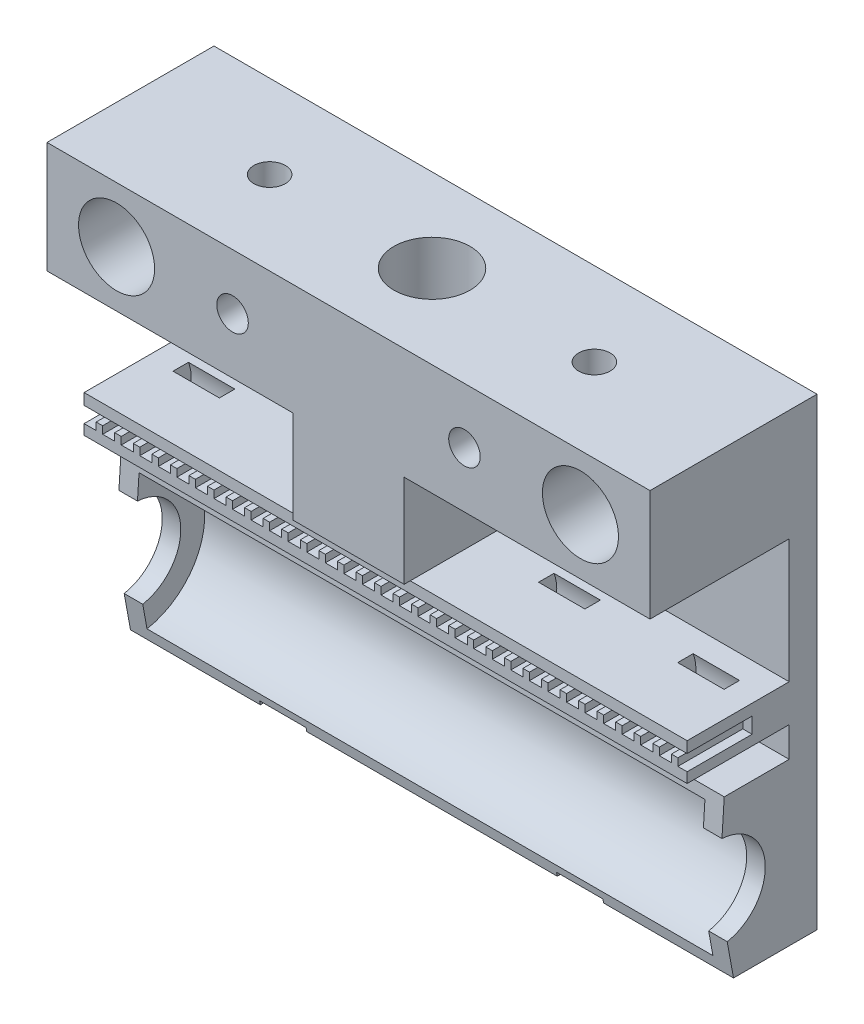
SolidWorks part; units mm, degrees
ref_plane "Ebene vorne" through (0, 0, 0) normal (0, 0, 1) x (1, 0, 0)
ref_plane "Ebene oben" through (0, 0, 0) normal (0, 1, 0) x (1, 0, 0)
ref_plane "Ebene rechts" through (0, 0, 0) normal (1, 0, 0) x (0, 0, -1)
sketch "Skizze1" plane through (0, 0, 0) normal (0, 0, 1) x (1, 0, 0)
  line L1 (-32.5, 25) -> (32.5, 25)
  line L2 (-32.5, 25) -> (-32.5, -25)
  line L3 (-32.5, -25) -> (32.5, -25)
  line L4 (32.5, 25) -> (32.5, -25)
  line L5 (-32.5, 25) -> (32.5, -25) construction
  line L6 (-32.5, -25) -> (32.5, 25) construction
  point P0 (0, 0)
  dimension "D1" = 65
  dimension "D2" = 50
extrude "Aufsatz-Linear austragen1" add sketch "Skizze1" along normal blind 3
sketch "Skizze2" plane through (0, 0, 3) normal (0, 0, 1) x (1, 0, 0)
  line L0 (32.5, -25) -> (32.5, 25) construction
  line L1 (-32.5, 25) -> (32.5, 25)
  line L2 (-32.5, 25) -> (-32.5, 13)
  line L3 (-32.5, 13) -> (32.5, 13)
  line L4 (32.5, 25) -> (32.5, 13)
  dimension "D1" = 12
extrude "Aufsatz-Linear austragen2" add sketch "Skizze2" along normal blind 15
sketch "Skizze3" plane through (0, 0, 18) normal (0, 0, 1) x (1, 0, 0)
  line L0 (32.5, 25) -> (-32.5, 25) construction
  line L1 (-32.5, 25) -> (-32.5, 13) construction
  line L2 (32.5, 13) -> (32.5, 25) construction
  circle A0 centre (-25, 19) radius 4.1
  circle A1 centre (25, 19) radius 4.1
  circle A2 centre (-12.5, 19) radius 1.7
  circle A3 centre (12.5, 19) radius 1.7
  point P6 (0, 25)
  dimension "D3" = 8.2
  dimension "D6" = 3.4
  dimension "D1" = 50
  dimension "D2" = 25
  dimension "D4" = 20
  dimension "D5" = 20
extrude "Schnitt-Linear austragen1" cut sketch "Skizze3" against normal up to next
sketch "Skizze4" plane through (0, 0, 0) normal (0, 0, -1) x (-1, 0, 0)
  line L0 (-32.5, -25) -> (-32.5, 25) construction
  line L1 (32.5, 25) -> (32.5, -25) construction
  point P0 (-12.5, 19)
  point P1 (12.5, 19)
  dimension "D1" = 20
  dimension "D2" = 20
sketch "Skizze7" plane through (0, 0, 0) normal (0, 0, -1) x (-1, 0, 0)
  line L0 (-32.5, 25) -> (32.5, 25) construction
  line L1 (-9.2091, 19) -> (-10.8546, 21.85)
  line L2 (-10.8546, 21.85) -> (-14.1454, 21.85)
  line L3 (-14.1454, 21.85) -> (-15.7909, 19)
  line L4 (-15.7909, 19) -> (-14.1454, 16.15)
  line L5 (-14.1454, 16.15) -> (-10.8546, 16.15)
  line L6 (-10.8546, 16.15) -> (-9.2091, 19)
  line L7 (15.7909, 19) -> (14.1454, 21.85)
  line L8 (14.1454, 21.85) -> (10.8546, 21.85)
  line L9 (10.8546, 21.85) -> (9.2091, 19)
  line L10 (9.2091, 19) -> (10.8546, 16.15)
  line L11 (10.8546, 16.15) -> (14.1454, 16.15)
  line L12 (14.1454, 16.15) -> (15.7909, 19)
  circle A0 centre (-12.5, 19) radius 2.85 construction
  circle A1 centre (12.5, 19) radius 2.85 construction
  dimension "D1" = 5.7
extrude "Schnitt-Linear austragen2" cut sketch "Skizze7" against normal blind 3.5
ref_plane "Ebene2" through (32.5, 0, 0) normal (-1, 0, 0) x (0, 0, 1)
sketch "Skizze10" plane through (32.5, 0, 0) normal (-1, 0, 0) x (0, 0, 1)
  line L0 (3, 13) -> (3, -25) construction
  line L2 (3, -25) -> (9, -25)
  line L3 (9, -25) -> (9.2184, -23.8)
  line L4 (3, -7.5887) -> (10, -7.5887)
  line L5 (10, -7.5887) -> (10.0788, -8.7887)
  line L6 (3, -7.5887) -> (3, -25)
  circle A0 centre (10.575, -16.3475) radius 7.575
  dimension "D1" = 15.15
  dimension "D3" = 6
  dimension "D4" = 7
  dimension "D5" = 1.2
  dimension "D6" = 1.2
extrude "Aufsatz-Linear austragen4" add sketch "Skizze10" along normal up to vertex (65 mm away) contours A0 L5 L4 L6 | A0 L6 L2 L3 up to point (-32.5, -25, 3)
sketch "Skizze11" plane through (32.5, 0, 0) normal (-1, 0, 0) x (0, 0, 1)
  line L0 (3, -7.5887) -> (10, -7.5887)
  line L1 (10, -7.5887) -> (10.2475, -11.3582)
  line L2 (3, -7.5887) -> (3, -25)
  line L3 (9, -25) -> (0, -25) construction
  line L4 (3, -25) -> (9, -25)
  line L5 (9, -25) -> (9.6796, -21.2666)
  circle A0 centre (10.575, -16.3475) radius 5
  dimension "D1" = 10
extrude "Aufsatz-Linear austragen5" add sketch "Skizze11" along normal blind 2 contours A0 L1 L0 L2 L4 L5
ref_plane "Ebene3" through (0, 0, 0) normal (1, 0, 0) x (0, 0, -1)
mirror "Spiegeln1" about plane through (0, 0, 0) normal (1, 0, 0) of "Aufsatz-Linear austragen5"
ref_axis "Achse1" through (-30.5, -16.3475, 10.575) along (1, 0, 0)
sketch "Skizze12" plane through (0, 0.6211, 9.461) normal (0, 0.0655, 0.9979) x (1, 0, 0)
  line L1 (-18.5, -7.1301) -> (-13.5, -7.1301)
  line L2 (-18.5, -7.1301) -> (-18.5, -8.6301)
  line L3 (-18.5, -8.6301) -> (-13.5, -8.6301)
  line L4 (-13.5, -7.1301) -> (-13.5, -8.6301)
  line L5 (-18.5, -7.1301) -> (-13.5, -8.6301) construction
  line L6 (-18.5, -8.6301) -> (-13.5, -7.1301) construction
  line L7 (0, -4.95) -> (0, 4.95) construction
  line L8 (-30.5, -9.4301) -> (30.5, -9.4301) construction
  point P0 (-16, -8.2275)
  dimension "D1" = 5
  dimension "D2" = 1.5
  dimension "D3" = 16
  dimension "D4" = 0.8
revolve "Schnitt-Rotation1" cut sketch "Skizze12" angle 360 about axis through (-30.5, -16.3475, 10.575) along (1, 0, 0)
mirror "Spiegeln2" about plane through (0, 0, 0) normal (1, 0, 0) of "Schnitt-Rotation1"
sketch "Skizze13" plane through (0, 0.6211, 9.461) normal (0, 0.0655, 0.9979) x (1, 0, 0)
  line L0 (-30.5, -9.4301) -> (30.5, -9.4301) construction
  line L1 (-17.3, -9.4301) -> (-16.5, -9.4301)
  line L2 (-17.3, -9.4301) -> (-17.3, -9.6301)
  line L3 (-17.3, -9.6301) -> (-16.5, -9.6301)
  line L4 (-16.5, -9.4301) -> (-16.5, -9.6301)
  line L5 (0, -4.95) -> (0, 4.95) construction
  dimension "D1" = 16.5
  dimension "D2" = 0.8
  dimension "D3" = 0.2
revolve "Rotation1" [suppressed] add sketch "Skizze13" about axis through (-30.5, -16.3475, 10.575) along (1, 0, 0)
mirror "Spiegeln3" [suppressed] about plane through (0, 0, 0) normal (1, 0, 0)
sketch "Skizze14" plane through (0, 0, 3) normal (0, 0, 1) x (1, 0, 0)
  line L0 (-32.5, 13) -> (-32.5, -7.5887) construction
  line L1 (-32.5, -0.3475) -> (32.5, -0.3475)
  line L2 (-32.5, -0.3475) -> (-32.5, -4.3475)
  line L3 (-32.5, -4.3475) -> (32.5, -4.3475)
  line L4 (32.5, -0.3475) -> (32.5, -4.3475)
  line L5 (32.5, 9.9) -> (32.5, -9.9) construction
  line L6 (-30.5, -16.3475) -> (30.5, -16.3475) construction
  point P10 (-32.5, -2.3475)
  dimension "D1" = 14
  dimension "D2" = 4
extrude "Aufsatz-Linear austragen6" add sketch "Skizze14" along normal blind 4
sketch "Skizze15" plane through (0, 0, 7) normal (0, 0, 1) x (1, 0, 0)
  line L0 (32.5, 9.9) -> (32.5, -9.9) construction
  line L1 (-32.5, -0.3475) -> (32.5, -0.3475)
  line L2 (-32.5, -0.3475) -> (-32.5, -1.5475)
  line L3 (-32.5, -1.5475) -> (32.5, -1.5475)
  line L4 (32.5, -0.3475) -> (32.5, -1.5475)
  line L6 (-32.5, -4.3475) -> (32.5, -4.3475)
  line L7 (-32.5, -4.3475) -> (-32.5, -2.4475)
  line L8 (-32.5, -2.4475) -> (32.5, -2.4475)
  line L9 (32.5, -4.3475) -> (32.5, -2.4475)
  dimension "D1" = 1.2
  dimension "D2" = 0.9
extrude "Aufsatz-Linear austragen7" add sketch "Skizze15" along normal blind 7
sketch "Skizze16" plane through (0, 0, 14) normal (0, 0, 1) x (1, 0, 0)
  line L0 (-32.5, -3.2475) -> (-31.2, -3.2475)
  line L1 (-32.5, -4.3475) -> (-32.5, -7.5887) construction
  line L2 (-31.2, -3.2475) -> (-31.2, -2.4475)
  line L3 (-31.2, -2.4475) -> (-30.5, -2.4475)
  line L4 (-30.5, -2.4475) -> (-30.5, -3.2475)
  line L5 (-30.5, -3.2475) -> (-29.2, -3.2475)
  line L6 (-29.2, -3.2475) -> (-29.2, -2.4475)
  line L7 (-29.2, -2.4475) -> (-28.5, -2.4475)
  line L8 (-28.5, -2.4475) -> (-28.5, -3.2475)
  line L10 (-28.5, -3.2475) -> (-27.2, -3.2475)
  line L11 (-27.2, -3.2475) -> (-27.2, -2.4475)
  line L12 (-27.2, -2.4475) -> (-26.5, -2.4475)
  line L13 (-26.5, -2.4475) -> (-26.5, -3.2475)
  line L14 (-25.2, -3.2475) -> (-25.2, -2.4475)
  line L15 (-25.2, -2.4475) -> (-24.5, -2.4475)
  line L16 (-24.5, -2.4475) -> (-24.5, -3.2475)
  line L17 (-26.5, -3.2475) -> (-25.2, -3.2475)
  line L18 (-24.5, -3.2475) -> (-23.2, -3.2475)
  line L19 (-23.2, -3.2475) -> (-23.2, -2.4475)
  line L20 (-23.2, -2.4475) -> (-22.5, -2.4475)
  line L21 (-22.5, -2.4475) -> (-22.5, -3.2475)
  line L22 (-21.2, -3.2475) -> (-21.2, -2.4475)
  line L23 (-21.2, -2.4475) -> (-20.5, -2.4475)
  line L24 (-20.5, -2.4475) -> (-20.5, -3.2475)
  line L25 (-22.5, -3.2475) -> (-21.2, -3.2475)
  line L26 (-20.5, -3.2475) -> (-19.2, -3.2475)
  line L27 (-19.2, -3.2475) -> (-19.2, -2.4475)
  line L28 (-19.2, -2.4475) -> (-18.5, -2.4475)
  line L29 (-18.5, -2.4475) -> (-18.5, -3.2475)
  line L30 (-17.2, -3.2475) -> (-17.2, -2.4475)
  line L31 (-17.2, -2.4475) -> (-16.5, -2.4475)
  line L32 (-16.5, -2.4475) -> (-16.5, -3.2475)
  line L33 (-18.5, -3.2475) -> (-17.2, -3.2475)
  line L34 (-16.5, -3.2475) -> (-15.2, -3.2475)
  line L35 (-15.2, -3.2475) -> (-15.2, -2.4475)
  line L36 (-15.2, -2.4475) -> (-14.5, -2.4475)
  line L37 (-14.5, -2.4475) -> (-14.5, -3.2475)
  line L38 (-13.2, -3.2475) -> (-13.2, -2.4475)
  line L39 (-13.2, -2.4475) -> (-12.5, -2.4475)
  line L40 (-12.5, -2.4475) -> (-12.5, -3.2475)
  line L41 (-14.5, -3.2475) -> (-13.2, -3.2475)
  line L42 (-12.5, -3.2475) -> (-11.2, -3.2475)
  line L43 (-11.2, -3.2475) -> (-11.2, -2.4475)
  line L44 (-11.2, -2.4475) -> (-10.5, -2.4475)
  line L45 (-10.5, -2.4475) -> (-10.5, -3.2475)
  line L46 (-9.2, -3.2475) -> (-9.2, -2.4475)
  line L47 (-9.2, -2.4475) -> (-8.5, -2.4475)
  line L48 (-8.5, -2.4475) -> (-8.5, -3.2475)
  line L49 (-10.5, -3.2475) -> (-9.2, -3.2475)
  line L50 (-8.5, -3.2475) -> (-7.2, -3.2475)
  line L51 (-7.2, -3.2475) -> (-7.2, -2.4475)
  line L52 (-7.2, -2.4475) -> (-6.5, -2.4475)
  line L53 (-6.5, -2.4475) -> (-6.5, -3.2475)
  line L54 (-5.2, -3.2475) -> (-5.2, -2.4475)
  line L55 (-5.2, -2.4475) -> (-4.5, -2.4475)
  line L56 (-4.5, -2.4475) -> (-4.5, -3.2475)
  line L57 (-6.5, -3.2475) -> (-5.2, -3.2475)
  line L58 (-4.5, -3.2475) -> (-3.2, -3.2475)
  line L59 (-3.2, -3.2475) -> (-3.2, -2.4475)
  line L60 (-3.2, -2.4475) -> (-2.5, -2.4475)
  line L61 (-2.5, -2.4475) -> (-2.5, -3.2475)
  line L62 (-1.2, -3.2475) -> (-1.2, -2.4475)
  line L63 (-1.2, -2.4475) -> (-0.5, -2.4475)
  line L64 (-0.5, -2.4475) -> (-0.5, -3.2475)
  line L65 (-2.5, -3.2475) -> (-1.2, -3.2475)
  line L66 (-0.5, -3.2475) -> (0.8, -3.2475)
  line L67 (0.8, -3.2475) -> (0.8, -2.4475)
  line L68 (0.8, -2.4475) -> (1.5, -2.4475)
  line L69 (1.5, -2.4475) -> (1.5, -3.2475)
  line L70 (2.8, -3.2475) -> (2.8, -2.4475)
  line L71 (2.8, -2.4475) -> (3.5, -2.4475)
  line L72 (3.5, -2.4475) -> (3.5, -3.2475)
  line L73 (1.5, -3.2475) -> (2.8, -3.2475)
  line L74 (3.5, -3.2475) -> (4.8, -3.2475)
  line L75 (4.8, -3.2475) -> (4.8, -2.4475)
  line L76 (4.8, -2.4475) -> (5.5, -2.4475)
  line L77 (5.5, -2.4475) -> (5.5, -3.2475)
  line L78 (6.8, -3.2475) -> (6.8, -2.4475)
  line L79 (6.8, -2.4475) -> (7.5, -2.4475)
  line L80 (7.5, -2.4475) -> (7.5, -3.2475)
  line L81 (5.5, -3.2475) -> (6.8, -3.2475)
  line L82 (7.5, -3.2475) -> (8.8, -3.2475)
  line L83 (8.8, -3.2475) -> (8.8, -2.4475)
  line L84 (8.8, -2.4475) -> (9.5, -2.4475)
  line L85 (9.5, -2.4475) -> (9.5, -3.2475)
  line L86 (10.8, -3.2475) -> (10.8, -2.4475)
  line L87 (10.8, -2.4475) -> (11.5, -2.4475)
  line L88 (11.5, -2.4475) -> (11.5, -3.2475)
  line L89 (9.5, -3.2475) -> (10.8, -3.2475)
  line L90 (11.5, -3.2475) -> (12.8, -3.2475)
  line L91 (12.8, -3.2475) -> (12.8, -2.4475)
  line L92 (12.8, -2.4475) -> (13.5, -2.4475)
  line L93 (13.5, -2.4475) -> (13.5, -3.2475)
  line L94 (14.8, -3.2475) -> (14.8, -2.4475)
  line L95 (14.8, -2.4475) -> (15.5, -2.4475)
  line L96 (15.5, -2.4475) -> (15.5, -3.2475)
  line L97 (13.5, -3.2475) -> (14.8, -3.2475)
  line L98 (15.5, -3.2475) -> (16.8, -3.2475)
  line L99 (16.8, -3.2475) -> (16.8, -2.4475)
  line L100 (16.8, -2.4475) -> (17.5, -2.4475)
  line L101 (17.5, -2.4475) -> (17.5, -3.2475)
  line L102 (18.8, -3.2475) -> (18.8, -2.4475)
  line L103 (18.8, -2.4475) -> (19.5, -2.4475)
  line L104 (19.5, -2.4475) -> (19.5, -3.2475)
  line L105 (17.5, -3.2475) -> (18.8, -3.2475)
  line L106 (19.5, -3.2475) -> (20.8, -3.2475)
  line L107 (20.8, -3.2475) -> (20.8, -2.4475)
  line L108 (20.8, -2.4475) -> (21.5, -2.4475)
  line L109 (21.5, -2.4475) -> (21.5, -3.2475)
  line L110 (22.8, -3.2475) -> (22.8, -2.4475)
  line L111 (22.8, -2.4475) -> (23.5, -2.4475)
  line L112 (23.5, -2.4475) -> (23.5, -3.2475)
  line L113 (21.5, -3.2475) -> (22.8, -3.2475)
  line L114 (23.5, -3.2475) -> (24.8, -3.2475)
  line L115 (24.8, -3.2475) -> (24.8, -2.4475)
  line L116 (24.8, -2.4475) -> (25.5, -2.4475)
  line L117 (25.5, -2.4475) -> (25.5, -3.2475)
  line L118 (26.8, -3.2475) -> (26.8, -2.4475)
  line L119 (26.8, -2.4475) -> (27.5, -2.4475)
  line L120 (27.5, -2.4475) -> (27.5, -3.2475)
  line L121 (25.5, -3.2475) -> (26.8, -3.2475)
  line L122 (27.5, -3.2475) -> (28.8, -3.2475)
  line L123 (28.8, -3.2475) -> (28.8, -2.4475)
  line L124 (28.8, -2.4475) -> (29.5, -2.4475)
  line L125 (29.5, -2.4475) -> (29.5, -3.2475)
  line L126 (30.8, -3.2475) -> (30.8, -2.4475)
  line L127 (30.8, -2.4475) -> (31.5, -2.4475)
  line L128 (31.5, -2.4475) -> (31.5, -3.2475)
  line L129 (29.5, -3.2475) -> (30.8, -3.2475)
  line L130 (31.5, -3.2475) -> (32.8, -3.2475)
  line L131 (32.8, -3.2475) -> (32.8, -2.3975)
  line L132 (32.8, -2.3975) -> (-32.5, -2.3975)
  line L133 (-32.5, -2.4475) -> (-32.5, -4.3475) construction
  line L134 (-32.5, -2.3975) -> (-32.5, -3.2475)
  line L138 (32.8, -3.2475) -> (32.8, -2.4475) [skipped]
  line L139 (32.8, -2.4475) -> (33.5, -2.4475) [skipped]
  line L140 (33.5, -2.4475) -> (33.5, -3.2475) [skipped]
  line L141 (34.8, -3.2475) -> (34.8, -2.4475) [skipped]
  line L142 (34.8, -2.4475) -> (35.5, -2.4475) [skipped]
  line L143 (35.5, -2.4475) -> (35.5, -3.2475) [skipped]
  line L144 (33.5, -3.2475) -> (34.8, -3.2475) [skipped]
  point P13 (-30.85, -2.4475)
  point P14 (-28.85, -2.4475)
  dimension "D1" = 2
  dimension "D2" = 0.7
  dimension "D3" = 0.8
  dimension "D4" = 0.8
  dimension "D5" = 17
  dimension "D6" = 0.85
extrude "Schnitt-Linear austragen4" cut sketch "Skizze16" against normal blind 7
sketch "Skizze18" plane through (0, 25, 0) normal (0, 1, 0) x (1, 0, 0)
  line L0 (-17.5, -9) -> (17.5, -9) construction
  circle A0 centre (-17.5, -9) radius 1.7
  circle A1 centre (17.5, -9) radius 1.7
  point P4 (0, -9)
  dimension "D1" = 3.4
  dimension "D2" = 35
extrude "Schnitt-Linear austragen5" cut sketch "Skizze18" against normal up to next
sketch "Skizze19" plane through (0, 13, 0) normal (0, -1, 0) x (1, 0, 0)
  line L7 (-14.2091, 9) -> (-15.8546, 11.85)
  line L8 (-15.8546, 11.85) -> (-19.1454, 11.85)
  line L9 (-19.1454, 11.85) -> (-20.7909, 9)
  line L10 (-20.7909, 9) -> (-19.1454, 6.15)
  line L11 (-19.1454, 6.15) -> (-15.8546, 6.15)
  line L12 (-15.8546, 6.15) -> (-14.2091, 9)
  circle A1 centre (-17.5, 9) radius 2.85 construction
  dimension "D1" = 5.7
extrude "Schnitt-Linear austragen6" cut sketch "Skizze19" against normal blind 3.5
mirror "Spiegeln4" about plane through (0, 0, 0) normal (1, 0, 0) of "Schnitt-Linear austragen6"
sketch "Skizze20" plane through (-32.5, 0, 0) normal (-1, 0, 0) x (0, 0, 1)
  line L0 (14, -3.2475) -> (5.8, -0.7475) construction
  line L3 (14, -0.7475) -> (5.8, -3.2475) construction
  line L4 (7, -1.5475) -> (7, -3.2475) construction
  line L5 (14, -1.5475) -> (7, -1.5475) construction
  line L6 (7, -3.2475) -> (14, -3.2475) construction
  line L8 (14, -0.3475) -> (14, -1.5475) construction
  point P24 (9.9, -1.9975)
  dimension "D1" = 1.2
  dimension "D2" = 0.8
  dimension "D3" = 0
ref_axis "Achse2" through (-32.5, -1.9975, 9.9) along (-1, 0, 0)
ref_plane "Ebene4" through (0, 0, 9.9) normal (0, 0, 1) x (1, 0, 0)
sketch "Skizze22" plane through (0, 0, 9.9) normal (0, 0, 1) x (1, 0, 0)
  line L1 (-29.7, 2.6525) -> (-24.7, 2.6525)
  line L2 (-29.7, 2.6525) -> (-29.7, 1.1525)
  line L3 (-29.7, 1.1525) -> (-24.7, 1.1525)
  line L4 (-24.7, 2.6525) -> (-24.7, 1.1525)
  line L5 (-29.7, 2.6525) -> (-24.7, 1.1525) construction
  line L6 (-29.7, 1.1525) -> (-24.7, 2.6525) construction
  line L7 (-32.5, 13) -> (-32.5, -0.3475) construction
  line L8 (32.5, -0.3475) -> (-32.5, -0.3475) construction
  point P0 (-20, -0.3475)
  dimension "D1" = 5
  dimension "D2" = 1.5
  dimension "D3" = 2.8
  dimension "D4" = 1.5
revolve "Schnitt-Rotation2" cut sketch "Skizze22" angle 180 about axis through (-32.5, -1.9975, 9.9) along (-1, 0, 0)
pattern_linear "Lineares Muster1" count 2 spacing 15 along (1, 0, 0) of "Schnitt-Rotation2"
mirror "Spiegeln5" about plane through (0, 0, 0) normal (1, 0, 0) of "Lineares Muster1", "Schnitt-Rotation2"
sketch "Skizze25" plane through (0, 0, 3) normal (0, 0, 1) x (1, 0, 0)
  line L0 (0, -4.95) -> (0, 4.95) construction
  line L1 (-6, 13) -> (6, 13)
  line L2 (-6, 13) -> (-6, 3)
  line L3 (-6, 3) -> (6, 3)
  line L4 (6, 13) -> (6, 3)
  line L5 (-6, 13) -> (6, 3) construction
  line L6 (-6, 3) -> (6, 13) construction
  line L7 (-32.5, 13) -> (32.5, 13) construction
  point P0 (0, 8)
  dimension "D1" = 12
  dimension "D2" = 10
extrude "Aufsatz-Linear austragen8" add sketch "Skizze25" along normal through all
sketch "Skizze23" plane through (0, 25, 0) normal (0, 1, 0) x (1, 0, 0)
  line L0 (0, -4.95) -> (0, 4.95) construction
  line L1 (32.5, 0) -> (-32.5, 0) construction
  line L2 (-32.5, -18) -> (-32.5, 0) construction
  circle A0 centre (0, -9) radius 4.1
  point P7 (0, 0)
  point P11 (-32.5, -9)
  dimension "D1" = 8.2
extrude "Schnitt-Linear austragen7" cut sketch "Skizze23" against normal blind 20
